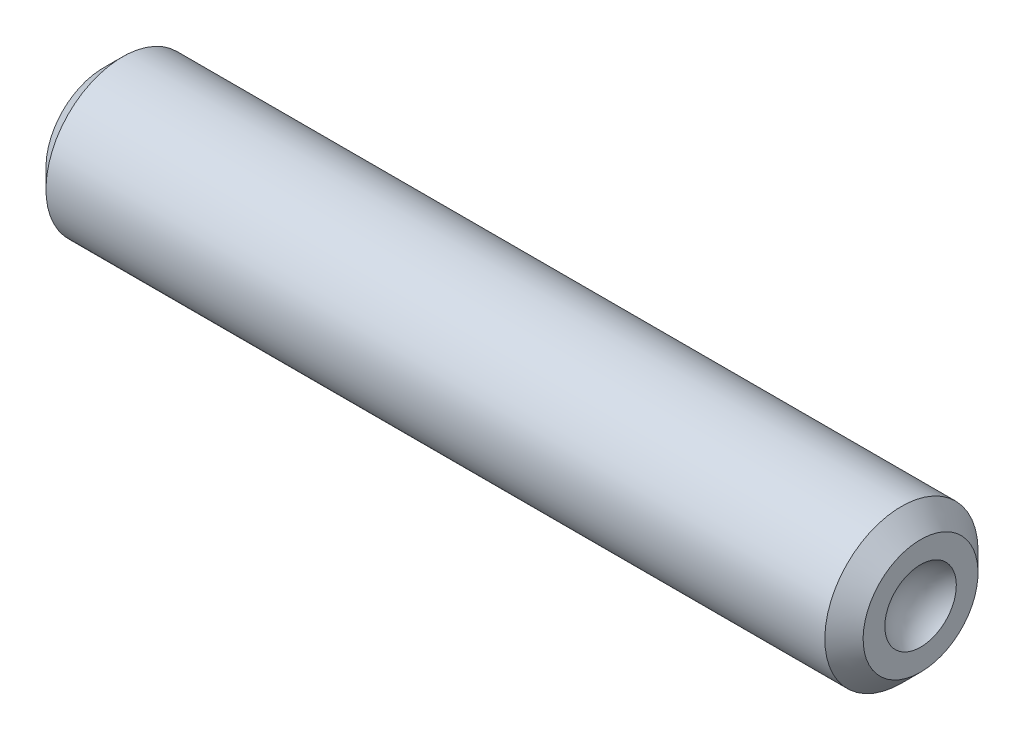
SolidWorks part; units mm, degrees
ref_plane "Front Plane" through (0, 0, 0) normal (0, 0, 1) x (1, 0, 0)
ref_plane "Top Plane" through (0, 0, 0) normal (0, 1, 0) x (1, 0, 0)
ref_plane "Right Plane" through (0, 0, 0) normal (1, 0, 0) x (0, 0, -1)
sketch "Sketch1" plane through (0, 0, 0) normal (0, 0, 1) x (1, 0, 0)
  line L0 (0, 0) -> (0, 1.125)
  line L1 (0, 1.125) -> (0.375, 1.5)
  line L2 (0.375, 1.5) -> (15.625, 1.5)
  line L3 (15.625, 1.5) -> (16, 1.125)
  line L4 (0, 0) -> (15.625, 0) construction
  line L5 (0.375, 1.5) -> (0.375, 1.125) construction
  line L6 (0.375, 1.125) -> (0.375, 0.75) construction
  line L7 (0.375, 0.75) -> (0.375, 0.375) construction
  line L8 (0.375, 0.375) -> (0.375, 0) construction
  line L9 (0.375, 1.125) -> (0, 1.125) construction
  line L10 (15.625, 1.5) -> (15.625, 0) construction
  line L11 (16, 1.125) -> (16, 0.7)
  line L12 (0, 0) -> (15.625, 0)
  arc A0 (15.625, 0) -> (16, 0.7) centre (16.4658, 0) cw
  dimension "D1" = 45
  dimension "D2" = 3
  dimension "D3" = 16
  dimension "D4" = 1.4
revolve "Revolve1" add sketch "Sketch1" angle 360 about L12
sketch "Sketch2" plane through (0, 0, 0) normal (-1, 0, 0) x (0, 0, 1)
  line L1 (0, 0.866) -> (-0.75, 0.433)
  line L2 (-0.75, 0.433) -> (-0.75, -0.433)
  line L3 (-0.75, -0.433) -> (0, -0.866)
  line L4 (0, -0.866) -> (0.75, -0.433)
  line L5 (0.75, -0.433) -> (0.75, 0.433)
  line L6 (0.75, 0.433) -> (0, 0.866)
  circle A0 centre (0, 0) radius 0.75 construction
  dimension "D1" = 1.5
extrude "Cut-Extrude1" cut sketch "Sketch2" against normal offset from surface (14 mm away) 2 up to face at (16, -1.125, 0)
